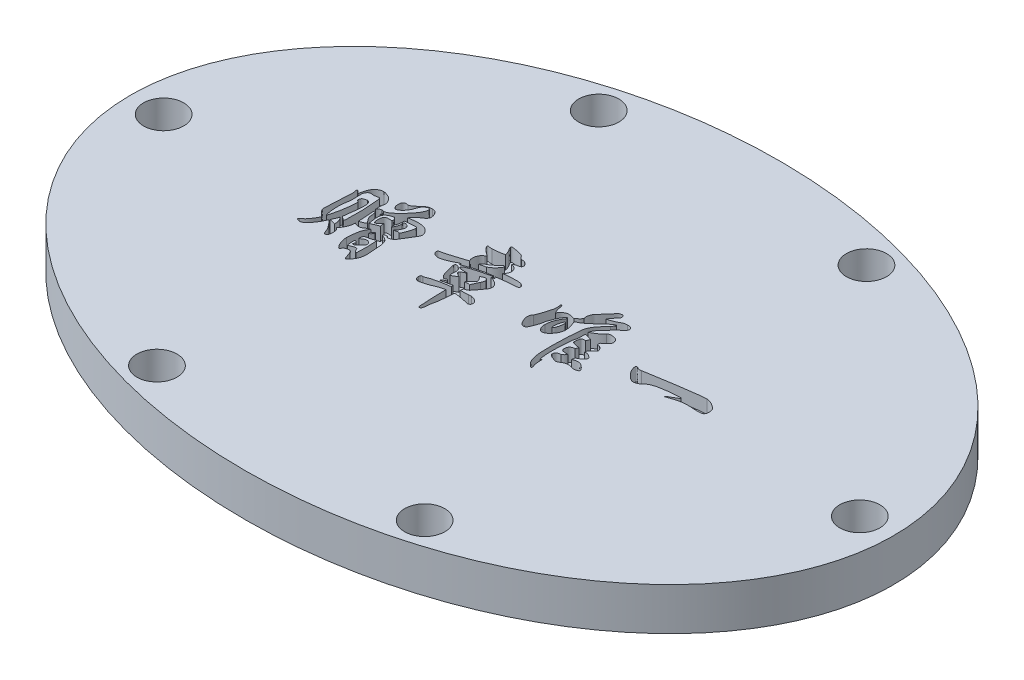
SolidWorks part; units mm, degrees
ref_plane "前视基准面" through (0, 0, 0) normal (0, 0, 1) x (1, 0, 0)
ref_plane "上视基准面" through (0, 0, 0) normal (0, 1, 0) x (1, 0, 0)
ref_plane "右视基准面" through (0, 0, 0) normal (1, 0, 0) x (0, 0, -1)
sketch "Sketch1" plane through (0, 0, 0) normal (0, 1, 0) x (1, 0, 0)
  line L0 (-41.2915, 0) -> (41.3233, 0) construction
  ellipse E0 centre (0.0159, 0) end of major axis (-28.4841, 0) minor radius 20
  dimension "D1" = 57
  dimension "D2" = 40
extrude "Boss-Extrude1" add sketch "Sketch1" along normal blind 3.175
sketch "Sketch2" plane through (0, 3.175, 0) normal (0, 1, 0) x (1, 0, 0)
  line L0 (-34.7429, 0) -> (37.6266, 0) construction
  line L1 (0, 13.4282) -> (0, -10.2791) construction
  circle A0 centre (-26, 0) radius 1.5
  circle A1 centre (26, 0) radius 1.5
  circle A2 centre (-10, 16.5) radius 1.5
  circle A3 centre (10, 16.5) radius 1.5
  circle A4 centre (10, -16.5) radius 1.5
  circle A5 centre (-10, -16.5) radius 1.5
  dimension "D1" = 3
  dimension "D3" = 3
  dimension "D2" = 52
  dimension "D4" = 20
  dimension "D5" = 33
extrude "Cut-Extrude1" cut sketch "Sketch2" against normal through all
sketch "Sketch3" plane through (0, 3.175, 0) normal (0, 1, 0) x (1, 0, 0)
  line L0 (-15.1948, -1.4854) -> (18.0786, -1.4854) construction
  text T0 "赠章唯一" font "华文行楷" height 5
  point P3 (-16.5614, -1.3666)
  point P4 (-13.8282, -1.3072)
  point P5 (0, 0)
  point P6 (-15.2542, -1.426)
  point P7 (18.0786, -1.4854)
  point P8 (-13.7094, -1.426)
  point P9 (-15.1948, -1.4854)
extrude "Cut-Extrude2" cut sketch "Sketch3" against normal blind 1
